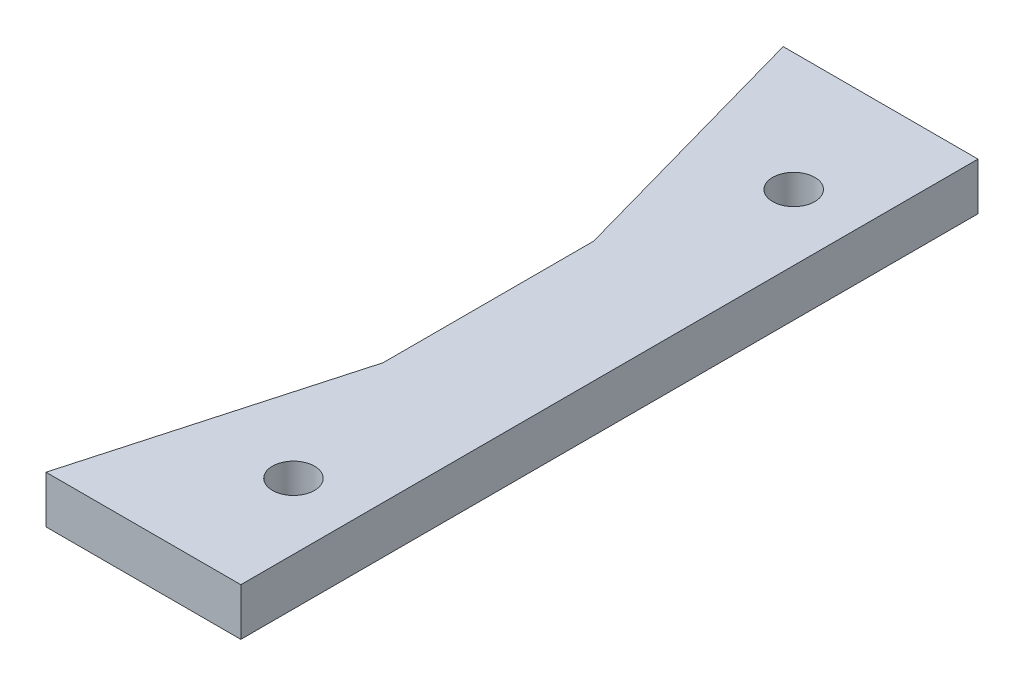
SolidWorks part; units mm, degrees
ref_plane "Front Plane" through (0, 0, 0) normal (0, 0, 1) x (1, 0, 0)
ref_plane "Top Plane" through (0, 0, 0) normal (0, 1, 0) x (1, 0, 0)
ref_plane "Right Plane" through (0, 0, 0) normal (1, 0, 0) x (0, 0, -1)
sketch "Sketch1" plane through (0, 0, 0) normal (0, 1, 0) x (1, 0, 0)
  line L0 (0, 75.8638) -> (0, -62.0943) construction
  line L1 (-37, 70) -> (0, 70)
  line L3 (-37, 70) -> (-23, 20)
  line L4 (-23, 20) -> (-23, 0)
  line L10 (-129.4117, 0) -> (46.5465, 0) construction
  line L11 (0, 70) -> (10, 70)
  line L12 (10, 70) -> (10, -70)
  line L13 (0, -70) -> (10, -70)
  line L14 (-23, -20) -> (-23, 0)
  line L15 (-37, -70) -> (-23, -20)
  line L16 (-37, -70) -> (0, -70)
  line L17 (0, 70) -> (0, -70)
  circle A0 centre (-12.5, 47.5) radius 4
  circle A4 centre (-12.5, -47.5) radius 4
  point P13 (0, 70)
  point P16 (10, 0)
  point P19 (-23, -10)
  point P20 (0, -70)
  point P21 (-30, 45)
  point P22 (-23, 10)
  dimension "D5" = 8
  dimension "D7" = 22.5
  dimension "D8" = 10
  dimension "D1" = 37
  dimension "D2" = 70
  dimension "D3" = 50
  dimension "D4" = 30
  dimension "D6" = 12.5
  dimension "D9" = 25
extrude "Boss-Extrude1" add sketch "Sketch1" along normal blind 9 contours L17 L1 L3 L4 L14 L15 L16 A0 A4
